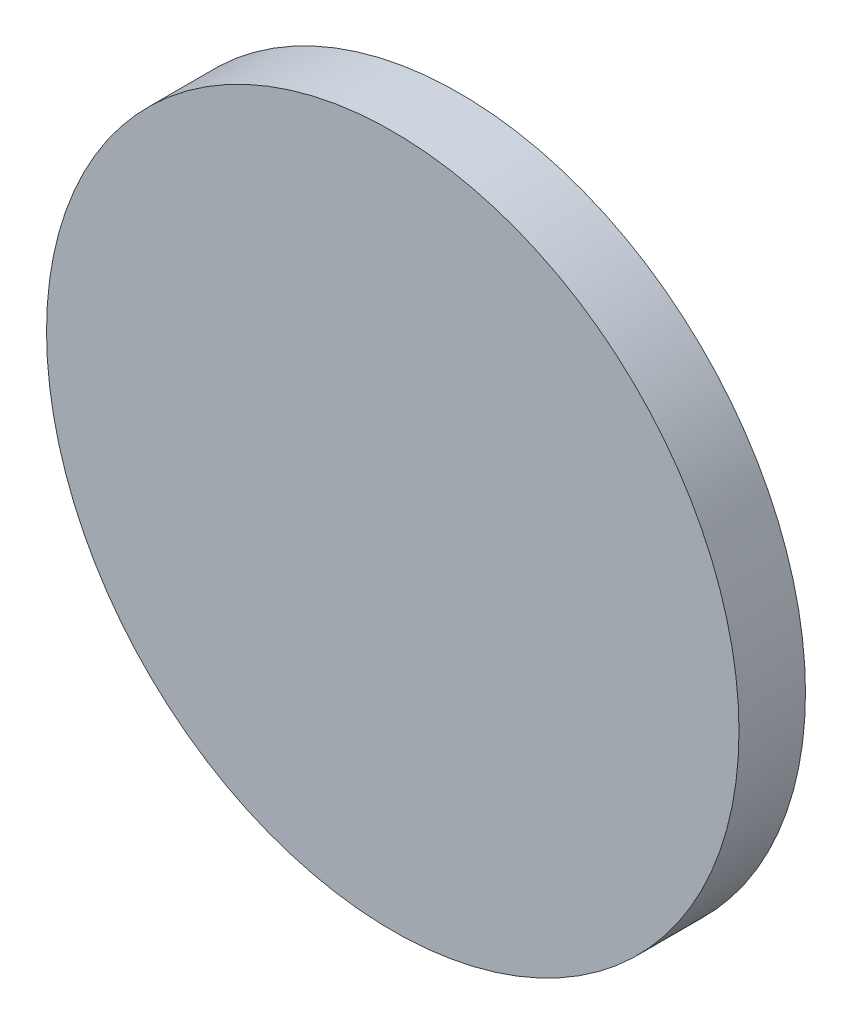
SolidWorks part; units mm, degrees
ref_plane "Front Plane" through (0, 0, 0) normal (0, 0, 1) x (1, 0, 0)
ref_plane "Top Plane" through (0, 0, 0) normal (0, 1, 0) x (1, 0, 0)
ref_plane "Right Plane" through (0, 0, 0) normal (1, 0, 0) x (0, 0, -1)
sketch "Sketch1" plane through (0, 0, 0) normal (0, 0, 1) x (1, 0, 0)
  circle A0 centre (0, 0) radius 12.5
  dimension "D1" = 25
extrude "Boss-Extrude1" add sketch "Sketch1" along normal blind 2.4
